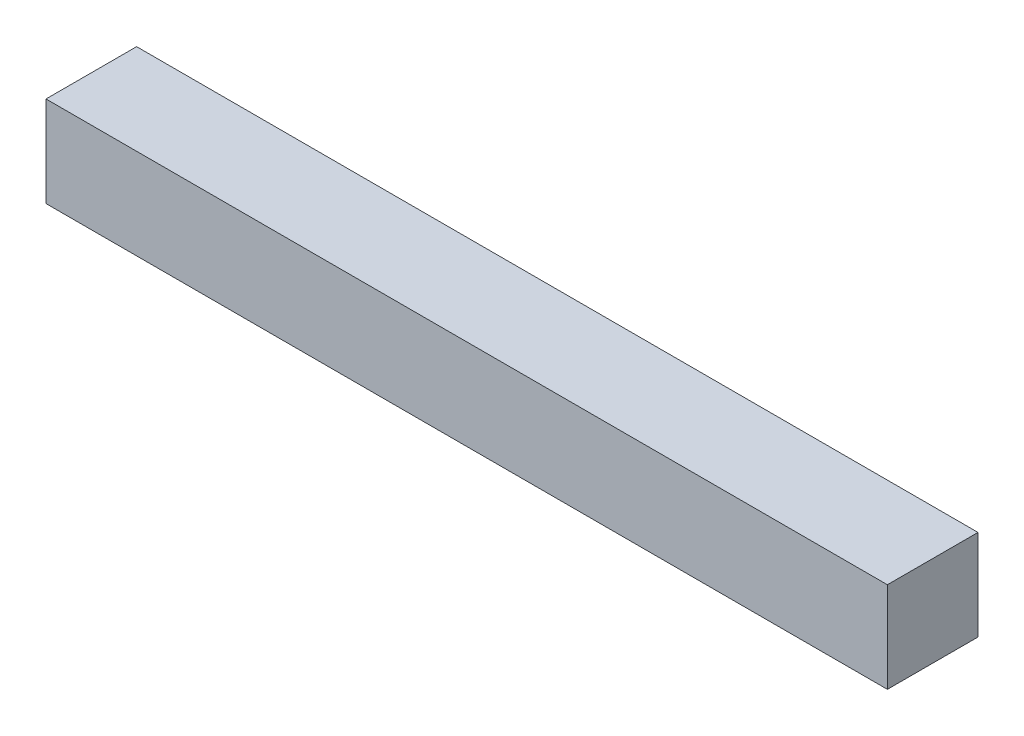
SolidWorks part; units mm, degrees
ref_plane "前视基准面" through (0, 0, 0) normal (0, 0, 1) x (1, 0, 0)
ref_plane "上视基准面" through (0, 0, 0) normal (0, 1, 0) x (1, 0, 0)
ref_plane "右视基准面" through (0, 0, 0) normal (1, 0, 0) x (0, 0, -1)
other "Configuration Table"
sketch "草图1" plane through (0, 0, 0) normal (0, 0, 1) x (1, 0, 0)
  line L1 (-130, -14) -> (130, -14)
  line L2 (-130, -14) -> (-130, 14)
  line L3 (-130, 14) -> (130, 14)
  line L4 (130, -14) -> (130, 14)
  line L5 (-130, -14) -> (130, 14) construction
  line L6 (-130, 14) -> (130, -14) construction
  point P0 (0, 0)
extrude "凸台-拉伸1" add sketch "草图1" along normal blind 28
